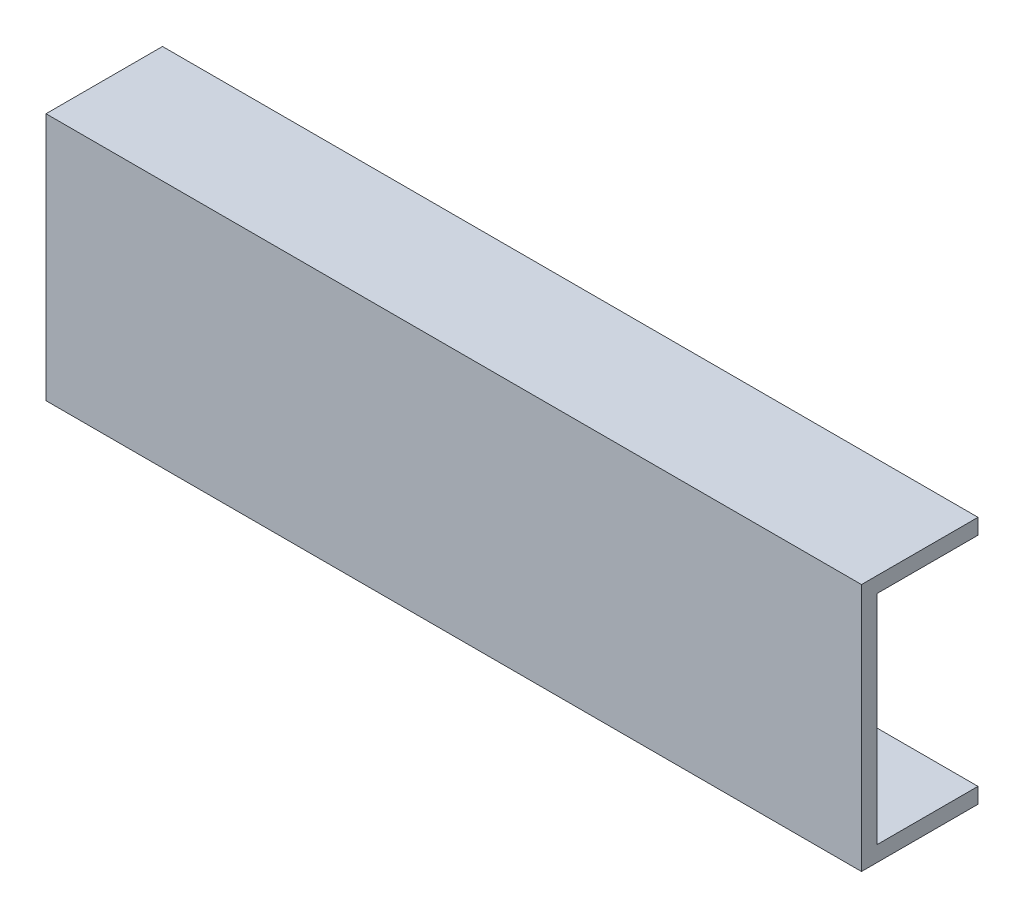
SolidWorks part; units mm, degrees
ref_plane "前基準面" through (0, 0, 0) normal (0, 0, 1) x (1, 0, 0)
ref_plane "上基準面" through (0, 0, 0) normal (0, 1, 0) x (1, 0, 0)
ref_plane "右基準面" through (0, 0, 0) normal (1, 0, 0) x (0, 0, -1)
sketch "草圖1" plane through (0, 0, 0) normal (0, 0, 1) x (1, 0, 0)
  line L1 (0, 0) -> (-105, 0)
  line L2 (0, 0) -> (0, 32)
  line L3 (0, 32) -> (-105, 32)
  line L4 (-105, 0) -> (-105, 32)
  dimension "D1" = 105
  dimension "D2" = 32
extrude "填料-伸長1" add sketch "草圖1" along normal blind 15
sketch "草圖3" plane through (0, 0, 0) normal (0, 0, -1) x (-1, 0, 0)
  line L0 (105, 0) -> (0, 0) construction
  line L1 (105, 2) -> (0, 2)
  line L2 (105, 2) -> (105, 30)
  line L3 (105, 30) -> (0, 30)
  line L4 (0, 2) -> (0, 30)
  line L5 (0, 0) -> (0, 32) construction
  line L6 (0, 32) -> (105, 32) construction
  dimension "D1" = 2
  dimension "D2" = 105
  dimension "D3" = 0
  dimension "D4" = 2
extrude "除料-伸長1" cut sketch "草圖3" against normal blind 13
